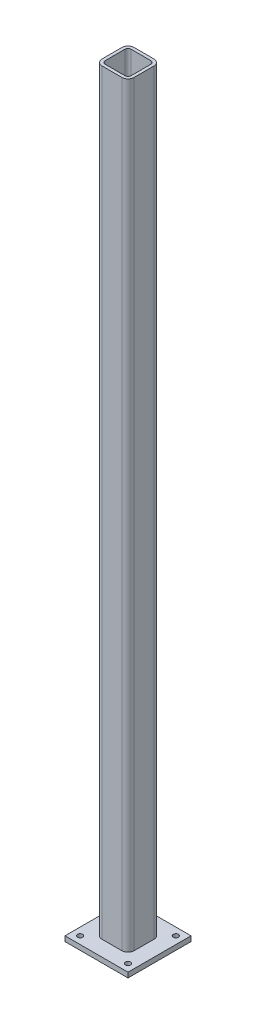
SolidWorks part; units mm, degrees
ref_plane "Płaszczyzna przednia" through (0, 0, 0) normal (0, 0, 1) x (1, 0, 0)
ref_plane "Płaszczyzna górna" through (0, 0, 0) normal (0, 1, 0) x (1, 0, 0)
ref_plane "Płaszczyzna prawa" through (0, 0, 0) normal (1, 0, 0) x (0, 0, -1)
sketch3d "Szkic 3D1"
  line L0 (0, 0, 0) -> (0, 1200, 0)
  dimension "D1" = 1200
other "Rura cienkościenna kwadratowa TS2X2X0.1875(1)"
ref_plane "Płaszczyzna1" through (0, 0, 0) normal (0, 1, 0) x (1, 0, 0)
sketch "Sketch12" plane through (0, 0, 0) normal (0, 1, 0) x (1, 0, 0)
  line L0 (-15.875, -20.6375) -> (15.875, -20.6375)
  line L1 (-20.6375, -15.875) -> (-20.6375, 15.875)
  line L2 (15.875, 20.6375) -> (-15.875, 20.6375)
  line L3 (20.6375, 15.875) -> (20.6375, -15.875)
  line L4 (-15.875, -25.4) -> (15.875, -25.4)
  line L5 (-25.4, -15.875) -> (-25.4, 15.875)
  line L6 (15.875, 25.4) -> (-15.875, 25.4)
  line L7 (25.4, 15.875) -> (25.4, -15.875)
  line L8 (-25.4, 0) -> (-20.6375, 0) construction
  line L9 (-20.6375, 0) -> (20.6375, 0) construction
  line L10 (20.6375, 0) -> (25.4, 0) construction
  line L11 (0, 25.4) -> (0, 20.6375) construction
  line L12 (0, 20.6375) -> (0, -20.6375) construction
  line L13 (0, -20.6375) -> (0, -25.4) construction
  arc A0 (25.4, 15.875) -> (15.875, 25.4) centre (15.875, 15.875) ccw
  arc A1 (15.875, -25.4) -> (25.4, -15.875) centre (15.875, -15.875) ccw
  arc A2 (-25.4, -15.875) -> (-15.875, -25.4) centre (-15.875, -15.875) ccw
  arc A3 (-15.875, 25.4) -> (-25.4, 15.875) centre (-15.875, 15.875) ccw
  arc A4 (-15.875, 20.6375) -> (-20.6375, 15.875) centre (-15.875, 15.875) ccw
  arc A5 (20.6375, 15.875) -> (15.875, 20.6375) centre (15.875, 15.875) ccw
  arc A6 (15.875, -20.6375) -> (20.6375, -15.875) centre (15.875, -15.875) ccw
  arc A7 (-20.6375, -15.875) -> (-15.875, -20.6375) centre (-15.875, -15.875) ccw
  point P6 (-25.4, -25.4)
  point P33 (-25.4, 25.4)
  point P35 (25.4, 25.4)
  point P36 (25.4, -25.4)
  point P37 (0, 0)
  point P38 (0, 0)
  dimension "D1" = 9.525
  dimension "Thickness" = 4.7625
  dimension "V_leg" = 50.8
  dimension "H_leg" = 50.8
sketch "Szkic4" plane through (0, 0, 0) normal (0, -1, 0) x (-1, 0, 0)
  line L1 (50, -50) -> (-50, -50)
  line L2 (50, -50) -> (50, 50)
  line L3 (50, 50) -> (-50, 50)
  line L4 (-50, -50) -> (-50, 50)
  line L5 (50, -50) -> (-50, 50) construction
  line L6 (50, 50) -> (-50, -50) construction
  circle A0 centre (38, -38) radius 4.1
  circle A1 centre (-38, -38) radius 4.1
  circle A2 centre (-38, 38) radius 4.1
  circle A3 centre (38, 38) radius 4.1
  point P0 (0, 0)
  dimension "D3" = 8.2
  dimension "D1" = 100
  dimension "D2" = 100
  dimension "D4" = 12
  dimension "D5" = 2
  dimension "D6" = 2
extrude "Dodanie-wyciągnięcie1" add sketch "Szkic4" along normal blind 8 separate body
